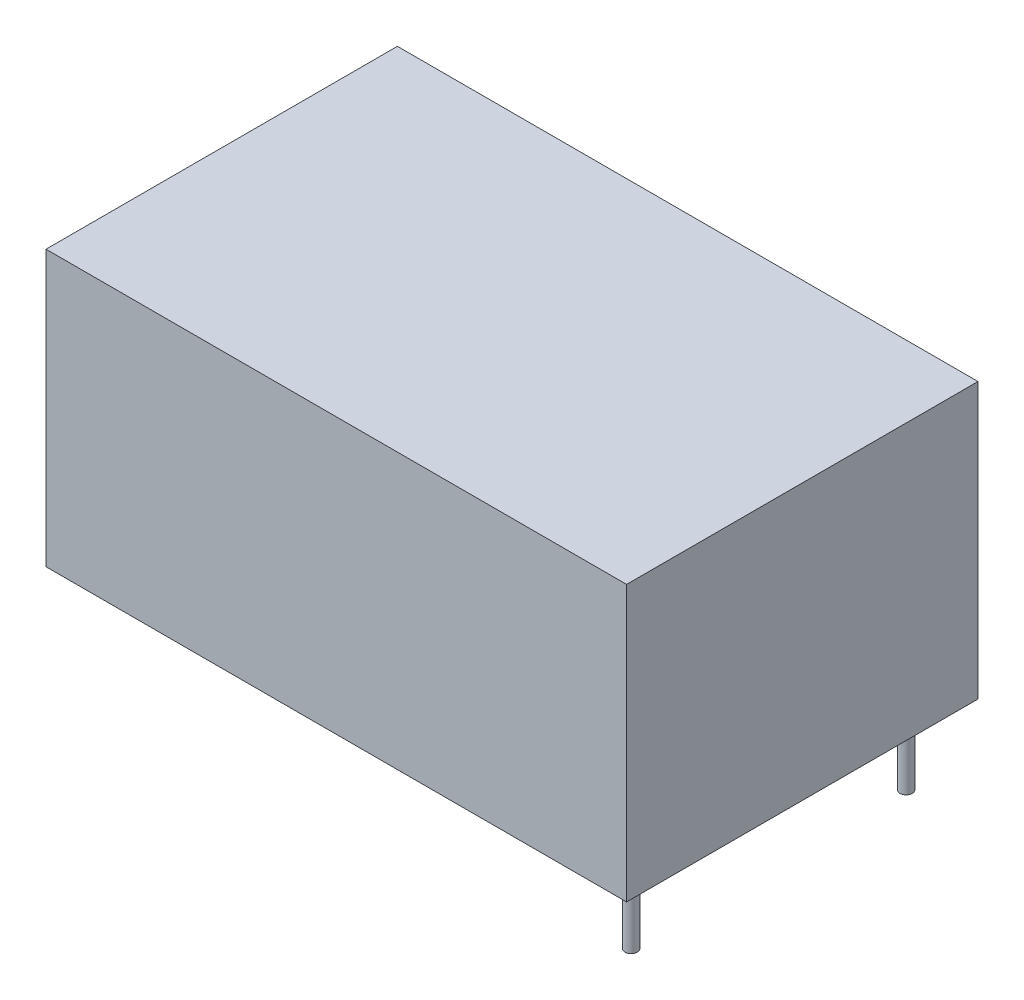
SolidWorks part; units mm, degrees
ref_plane "Front Plane" through (0, 0, 0) normal (0, 0, 1) x (1, 0, 0)
ref_plane "Top Plane" through (0, 0, 0) normal (0, 1, 0) x (1, 0, 0)
ref_plane "Right Plane" through (0, 0, 0) normal (1, 0, 0) x (0, 0, -1)
ref_plane "Plane1" through (0, 0, 0) normal (0, -1, 0) x (1, 0, 0)
sketch "Sketch1" plane through (0, 0, 0) normal (0, -1, 0) x (1, 0, 0)
  line L0 (-19, 10.5602) -> (-19, -12.4398)
  line L1 (-19, -12.4398) -> (19, -12.4398)
  line L2 (19, -12.4398) -> (19, 10.5602)
  line L3 (19, 10.5602) -> (-19, 10.5602)
  dimension "D1" = 38
  dimension "D2" = 23
extrude "Boss-Extrude1" add sketch "Sketch1" against normal blind 18
sketch "Sketch12" plane through (0, 0, 0) normal (0, -1, 0) x (1, 0, 0)
  line L0 (19, -0.9398) -> (-19, -0.9398) construction
  line L1 (19, -12.4398) -> (19, 10.5602) construction
  line L2 (-19, 10.5602) -> (-19, -12.4398) construction
  line L3 (16.8, 10.5602) -> (16.8, -12.4398) construction
  line L4 (19, 10.5602) -> (-19, 10.5602) construction
  line L5 (-19, -12.4398) -> (19, -12.4398) construction
  line L6 (-16.8, 10.5602) -> (-16.8, -12.4398) construction
  line L7 (-19, -12.4398) -> (19, -12.4398) construction
  line L8 (-19, 10.5602) -> (-19, -12.4398) construction
  point P14 (-16.8, 2.0602)
  point P15 (-16.8, -3.9398)
  point P16 (16.8, -9.9398)
  point P19 (16.8, 8.0602)
  dimension "D1" = 14.5
  dimension "D2" = 35.8
  dimension "D3" = 8.5
  dimension "D4" = 20.5
  dimension "D5" = 2.2
sketch "Sketch3" plane through (0, 0, 0) normal (0, -1, 0) x (1, 0, 0)
  circle A0 centre (16.8, -9.9398) radius 0.4
  dimension "D1" = 0.8
extrude "Boss-Extrude3" add sketch "Sketch3" along normal blind 5
sketch "Sketch4" plane through (0, 0, 0) normal (0, -1, 0) x (1, 0, 0)
  circle A0 centre (-16.8, -3.9398) radius 0.4
  dimension "D1" = 0.8
extrude "Boss-Extrude4" add sketch "Sketch4" along normal blind 5
sketch "Sketch5" plane through (0, 0, 0) normal (0, -1, 0) x (1, 0, 0)
  circle A0 centre (16.8, 8.0602) radius 0.4
  dimension "D1" = 0.8
extrude "Boss-Extrude5" add sketch "Sketch5" along normal blind 5
sketch "Sketch6" plane through (0, 0, 0) normal (0, -1, 0) x (1, 0, 0)
  circle A0 centre (-16.8, 2.0602) radius 0.4
  dimension "D1" = 0.8
extrude "Boss-Extrude6" add sketch "Sketch6" along normal blind 5
